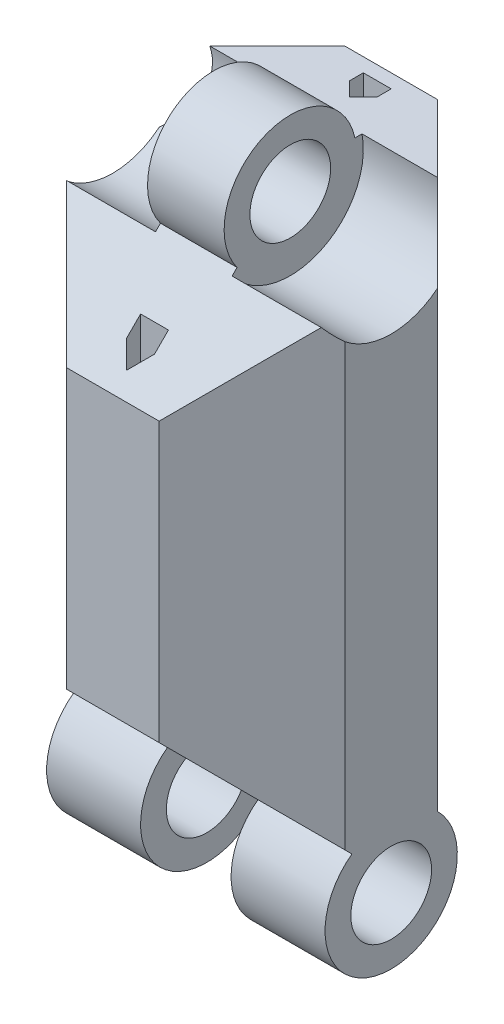
SolidWorks part; units mm, degrees
ref_plane "Front Plane" through (0, 0, 0) normal (0, 0, 1) x (1, 0, 0)
ref_plane "Top Plane" through (0, 0, 0) normal (0, 1, 0) x (1, 0, 0)
ref_plane "Right Plane" through (0, 0, 0) normal (1, 0, 0) x (0, 0, -1)
sketch "Sketch1" plane through (0, 0, 0) normal (0, 1, 0) x (1, 0, 0)
  line L0 (-1.6667, -5) -> (1.6667, -5)
  line L1 (1.6667, -5) -> (5, -1.6667)
  line L2 (5, -1.6667) -> (5, 1.6667)
  line L3 (5, 1.6667) -> (1.6667, 5)
  line L4 (1.6667, 5) -> (-1.6667, 5)
  line L5 (-1.6667, 5) -> (-5, 1.6667)
  line L6 (-5, 1.6667) -> (-5, -1.6667)
  line L7 (-5, -1.6667) -> (-1.6667, -5)
  point P2 (-23.4035, -6.4439)
  point P9 (0, 0)
  point P10 (0, 0)
  point P11 (0, 0)
  point P12 (0, 0)
  point P13 (-20.4677, -7.9197)
  point P14 (-21.0793, -7.5528)
  point P15 (-3.1432, 6.2245)
  point P16 (5, 0)
  point P18 (5.7476, -2.7846)
  point P19 (0, -5)
  point P20 (2.8311, 7.5)
  dimension "D1" = 135
  dimension "D2" = 10
  dimension "D3" = 10
  dimension "D4" = 3.3333
extrude "Boss-Extrude1" add sketch "Sketch1" along normal blind 20
sketch "Sketch2" plane through (0, 0, 0) normal (1, 0, 0) x (0, 0, -1)
  line L0 (0, 20) -> (-5, 20)
  line L1 (-1.6667, 20) -> (1.6667, 20) construction
  line L2 (-5, 20) -> (-5, 15)
  line L3 (-5, 20) -> (-5, 0) construction
  line L4 (-5, 15) -> (0, 20)
  line L5 (0, 0) -> (-5, 0)
  line L6 (-1.6667, 0) -> (1.6667, 0) construction
  line L7 (-5, 0) -> (-5, 5)
  line L8 (-5, 5) -> (0, 0)
  dimension "D1" = 45
  dimension "D2" = 45
extrude "Cut-Extrude1" cut sketch "Sketch2" against normal through all both and the other way through all contours L4 L0 L2 | L8 L5 L7
sketch "Sketch3" plane through (0, 0, 0) normal (0, 1, 0) x (1, 0, 0)
  line L0 (0, -4.5) -> (-0.5, -4)
  line L1 (-0.5, -4) -> (-0.5, -3.5)
  line L2 (-0.5, -3.5) -> (0.5, -3.5)
  line L3 (0.5, -3.5) -> (0.5, -4)
  line L4 (0.5, -4) -> (0, -4.5)
  line L5 (-1.6667, -5) -> (1.6667, -5) construction
  line L6 (0.5, 4.5) -> (0.5, 4)
  line L7 (-0.5, 4.5) -> (0.5, 4.5)
  line L8 (-0.5, 4) -> (-0.5, 4.5)
  line L9 (0, 3.5) -> (-0.5, 4)
  line L10 (0.5, 4) -> (0, 3.5)
  line L11 (1.6667, 5) -> (-1.6667, 5) construction
  point P2 (0.5, 4.6041)
  point P6 (0, -3.5)
  point P13 (0, -5)
  dimension "D1" = 1
  dimension "D2" = 0.5
  dimension "D3" = 0.5
  dimension "D4" = 0.5
  dimension "D5" = 0.5
  dimension "D6" = 2
  dimension "D7" = 0.5
extrude "Cut-Extrude2" cut sketch "Sketch3" along normal through all
sketch "Sketch4" plane through (0, 0, 0) normal (1, 0, 0) x (0, 0, -1)
  circle A0 centre (0, 19.5) radius 2.375
  dimension "D2" = 4.75
  dimension "D1" = 0.5
extrude "Boss-Extrude2" add sketch "Sketch4" along normal mid plane 2.75
sketch "Sketch5" plane through (1.375, 0, 0) normal (1, 0, 0) x (0, 0, -1)
  circle A0 centre (0, 19.5) radius 2.625
  dimension "D1" = 5.25
extrude "Cut-Extrude3" cut sketch "Sketch5" along normal through all
mirror "Mirror1" about plane through (0, 0, 0) normal (1, 0, 0) of "Cut-Extrude3"
sketch "Sketch6" plane through (0, 0, 0) normal (1, 0, 0) x (0, 0, -1)
  circle A0 centre (0, -0.5) radius 2.625
  dimension "D2" = 5.25
  dimension "D1" = 0.5
extrude "Cut-Extrude4" cut sketch "Sketch6" against normal mid plane 3.25
sketch "Sketch7" plane through (-1.625, 0, 0) normal (1, 0, 0) x (0, 0, -1)
  circle A0 centre (0, -0.5) radius 2.375
  dimension "D2" = 4.75
  dimension "D1" = 0.5
extrude "Boss-Extrude3" add sketch "Sketch7" against normal up to surface (3.375 mm away) up to face at (-5, 7.2027, 0)
sketch "Sketch8" plane through (1.625, 0, 0) normal (-1, 0, 0) x (0, 0, 1)
  circle A0 centre (0, -0.5) radius 2.375
  dimension "D2" = 4.75
  dimension "D1" = 0.5
extrude "Boss-Extrude4" add sketch "Sketch8" against normal up to surface (3.375 mm away) up to face at (5, 7.2027, 0)
sketch "Sketch10" plane through (1.375, 0, 0) normal (1, 0, 0) x (0, 0, -1)
  circle A0 centre (0, 19.5) radius 1.45
  dimension "D1" = 2.9
extrude "Cut-Extrude5" cut sketch "Sketch10" against normal through all both and the other way through all
sketch "Sketch11" plane through (5, 0, 0) normal (1, 0, 0) x (0, 0, -1)
  circle A0 centre (0, -0.5) radius 1.45
  dimension "D1" = 2.9
extrude "Cut-Extrude6" cut sketch "Sketch11" against normal through all both and the other way through all
